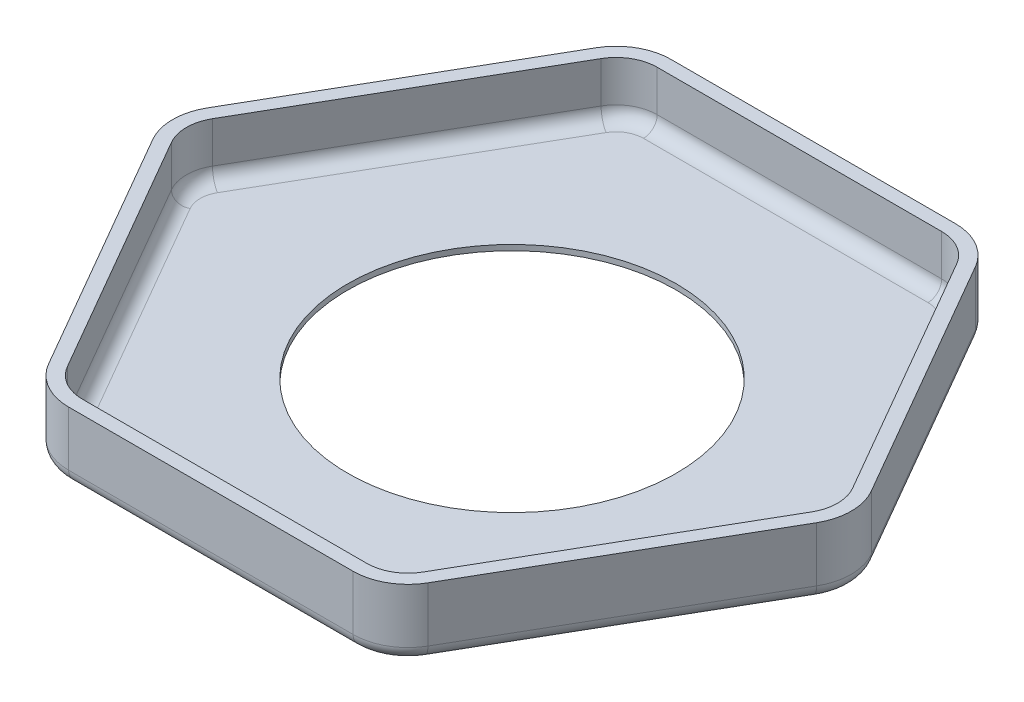
SolidWorks part; units mm, degrees
ref_plane "Front" through (0, 0, 0) normal (0, 0, 1) x (1, 0, 0)
ref_plane "Top" through (0, 0, 0) normal (0, 1, 0) x (1, 0, 0)
ref_plane "Right" through (0, 0, 0) normal (1, 0, 0) x (0, 0, -1)
sketch "Croquis1" plane through (0, 0, 0) normal (0, 1, 0) x (1, 0, 0)
  line L0 (-119.2242, -9.3942) -> (-67.2627, -99.3942)
  line L1 (-49.9422, -109.3942) -> (53.9809, -109.3942)
  line L2 (71.3014, -99.3942) -> (123.2629, -9.3942)
  line L3 (123.2629, 10.6058) -> (71.3014, 100.6058)
  line L4 (53.9809, 110.6058) -> (-49.9422, 110.6058)
  line L5 (-67.2627, 100.6058) -> (-119.2242, 10.6058)
  circle A0 centre (2.0194, 0.6058) radius 110 construction
  arc A1 (-67.2627, 100.6058) -> (-49.9422, 110.6058) centre (-49.9422, 90.6058) cw
  arc A2 (71.3014, 100.6058) -> (53.9809, 110.6058) centre (53.9809, 90.6058) ccw
  arc A3 (123.2629, -9.3942) -> (123.2629, 10.6058) centre (105.9424, 0.6058) ccw
  arc A4 (53.9809, -109.3942) -> (71.3014, -99.3942) centre (53.9809, -89.3942) ccw
  arc A5 (-67.2627, -99.3942) -> (-49.9422, -109.3942) centre (-49.9422, -89.3942) ccw
  arc A6 (-119.2242, -9.3942) -> (-119.2242, 10.6058) centre (-101.9037, 0.6058) cw
  dimension "D1" = 220
  dimension "D2" = 20
extrude "Saliente-Extruir2" add sketch "Croquis1" along normal blind 5
sketch "Croquis2" plane through (0, 5, 0) normal (0, 1, 0) x (1, 0, 0)
  line L6 (-62.9325, 98.1058) -> (-114.8941, 8.1058)
  line L7 (-114.8941, -6.8942) -> (-62.9325, -96.8942)
  line L8 (-49.9422, -104.3942) -> (53.9809, -104.3942)
  line L9 (66.9713, -96.8942) -> (118.9328, -6.8942)
  line L10 (118.9328, 8.1058) -> (66.9713, 98.1058)
  line L11 (53.9809, 105.6058) -> (-49.9422, 105.6058)
  line L12 (-67.2627, 100.6058) -> (-119.2242, 10.6058)
  line L13 (-119.2242, -9.3942) -> (-67.2627, -99.3942)
  line L14 (-49.9422, -109.3942) -> (53.9809, -109.3942)
  line L15 (71.3014, -99.3942) -> (123.2629, -9.3942)
  line L16 (123.2629, 10.6058) -> (71.3014, 100.6058)
  line L17 (53.9809, 110.6058) -> (-49.9422, 110.6058)
  line L18 (-67.2627, 100.6058) -> (-119.2242, 10.6058)
  line L19 (-119.2242, -9.3942) -> (-67.2627, -99.3942)
  line L20 (-49.9422, -109.3942) -> (53.9809, -109.3942)
  line L21 (71.3014, -99.3942) -> (123.2629, -9.3942)
  line L22 (123.2629, 10.6058) -> (71.3014, 100.6058)
  line L23 (53.9809, 110.6058) -> (-49.9422, 110.6058)
  arc A6 (-114.8941, 8.1058) -> (-114.8941, -6.8942) centre (-101.9037, 0.6058) ccw
  arc A7 (-62.9325, -96.8942) -> (-49.9422, -104.3942) centre (-49.9422, -89.3942) ccw
  arc A8 (53.9809, -104.3942) -> (66.9713, -96.8942) centre (53.9809, -89.3942) ccw
  arc A9 (118.9328, -6.8942) -> (118.9328, 8.1058) centre (105.9424, 0.6058) ccw
  arc A10 (66.9713, 98.1058) -> (53.9809, 105.6058) centre (53.9809, 90.6058) ccw
  arc A11 (-49.9422, 105.6058) -> (-62.9325, 98.1058) centre (-49.9422, 90.6058) ccw
  arc A12 (-49.9422, 110.6058) -> (-67.2627, 100.6058) centre (-49.9422, 90.6058) ccw
  arc A13 (-119.2242, 10.6058) -> (-119.2242, -9.3942) centre (-101.9037, 0.6058) ccw
  arc A14 (-67.2627, -99.3942) -> (-49.9422, -109.3942) centre (-49.9422, -89.3942) ccw
  arc A15 (53.9809, -109.3942) -> (71.3014, -99.3942) centre (53.9809, -89.3942) ccw
  arc A16 (123.2629, -9.3942) -> (123.2629, 10.6058) centre (105.9424, 0.6058) ccw
  arc A17 (71.3014, 100.6058) -> (53.9809, 110.6058) centre (53.9809, 90.6058) ccw
  arc A18 (-49.9422, 110.6058) -> (-67.2627, 100.6058) centre (-49.9422, 90.6058) ccw
  arc A19 (-119.2242, 10.6058) -> (-119.2242, -9.3942) centre (-101.9037, 0.6058) ccw
  arc A20 (-67.2627, -99.3942) -> (-49.9422, -109.3942) centre (-49.9422, -89.3942) ccw
  arc A21 (53.9809, -109.3942) -> (71.3014, -99.3942) centre (53.9809, -89.3942) ccw
  arc A22 (123.2629, -9.3942) -> (123.2629, 10.6058) centre (105.9424, 0.6058) ccw
  arc A23 (71.3014, 100.6058) -> (53.9809, 110.6058) centre (53.9809, 90.6058) ccw
  dimension "D1" = 0
  dimension "D2" = 5
extrude "Saliente-Extruir3" add sketch "Croquis2" along normal blind 20
fillet "Redondeo2" radius 5 12 edges at (-93.2434, 0, -55.6058) (-121.9037, 0, -0.6058) (-93.2434, 0, 54.3942) (-59.9422, 0, 106.7147) (2.0194, 0, 109.3942) (63.9809, 0, 106.7147) (97.2822, 0, 54.3942) (125.9424, 0, -0.6058) (97.2822, 0, -55.6058) (63.9809, 0, -107.9263) (2.0194, 0, -110.6058) (-59.9422, 0, -107.9263)
fillet "Redondeo3" radius 5 12 edges at (61.4809, 5, -103.5962) (92.952, 5, -53.1058) (120.9424, 5, -0.6058) (92.952, 5, 51.8942) (61.4809, 5, 102.3846) (2.0194, 5, 104.3942) (-57.4422, 5, 102.3846) (-88.9133, 5, 51.8942) (-116.9037, 5, -0.6058) (-88.9133, 5, -53.1058) (-57.4422, 5, -103.5962) (2.0194, 5, -105.6058)
sketch "Croquis3" plane through (0, 0, 0) normal (0, -1, 0) x (1, 0, 0)
  line L0 (-57.4422, 102.3846) -> (61.4809, -103.5962) construction
  line L1 (-57.4422, -103.5962) -> (61.4809, 102.3846) construction
  arc A0 (-49.9422, 104.3942) -> (-62.9325, 96.8942) centre (-49.9422, 89.3942) ccw construction
  arc A1 (53.9809, -105.6058) -> (66.9713, -98.1058) centre (53.9809, -90.6058) ccw construction
  arc A2 (-62.9325, -98.1058) -> (-49.9422, -105.6058) centre (-49.9422, -90.6058) ccw construction
  arc A3 (66.9713, 96.8942) -> (53.9809, 104.3942) centre (53.9809, 89.3942) ccw construction
  circle A4 centre (2.0194, -0.6058) radius 90
  point P18 (0, 0)
sketch "Croquis4" plane through (0, 0, 0) normal (0, -1, 0) x (-1, 0, 0)
  circle A0 centre (-2.0194, 0.6058) radius 60
extrude "Cortar-Extruir1" cut sketch "Croquis4" against normal blind 10
extrude "Cortar-Extruir2" cut sketch "Croquis3" against normal blind 3
